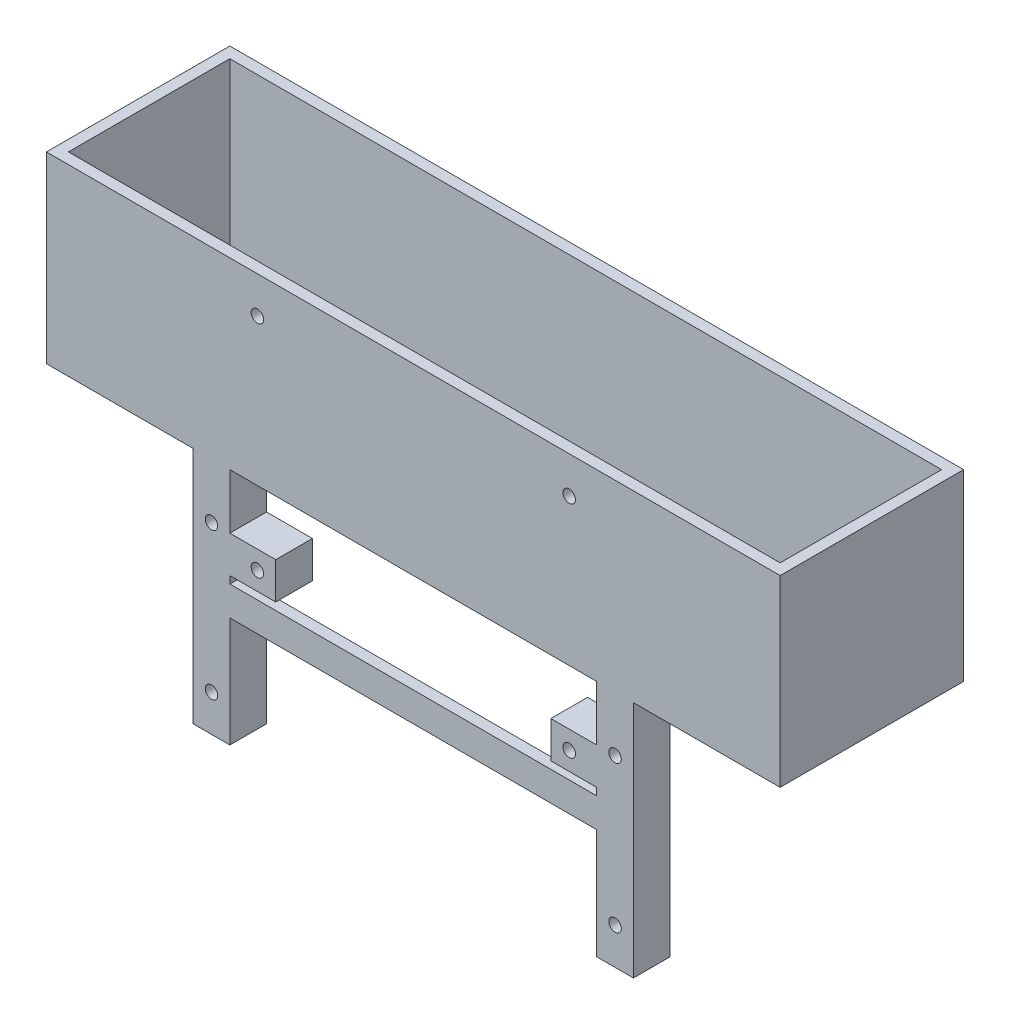
SolidWorks part; units mm, degrees
ref_plane "前视基准面" through (0, 0, 0) normal (0, 0, 1) x (1, 0, 0)
ref_plane "上视基准面" through (0, 0, 0) normal (0, 1, 0) x (1, 0, 0)
ref_plane "右视基准面" through (0, 0, 0) normal (1, 0, 0) x (0, 0, -1)
other "Configuration Table"
sketch "Box footprint 200 x 50 mm" plane through (0, 0, 0) normal (0, 0, 1) x (1, 0, 0)
  line L1 (-100, 0) -> (100, 0)
  line L2 (-100, 0) -> (-100, 50)
  line L3 (-100, 50) -> (100, 50)
  line L4 (100, 0) -> (100, 50)
extrude "Box height 50 mm" add sketch "Box footprint 200 x 50 mm" along normal blind 50
sketch "Rear opening 194 x 44 mm" plane through (0, 50, 0) normal (0, 1, 0) x (1, 0, 0)
  line L1 (-97, -3) -> (97, -3)
  line L2 (-97, -3) -> (-97, -47)
  line L3 (-97, -47) -> (97, -47)
  line L4 (97, -3) -> (97, -47)
extrude "Rear cavity wall 3 mm" cut sketch "Rear opening 194 x 44 mm" against normal blind 47
sketch "Chassis face openings and mounting crossbar" plane through (0, 0, 0) normal (0, -1, 0) x (1, 0, 0)
  line L1 (-97, 3) -> (-60, 3)
  line L2 (-97, 3) -> (-97, 47)
  line L3 (-97, 47) -> (-60, 47)
  line L4 (-60, 3) -> (-60, 47)
  line L6 (60, 3) -> (97, 3)
  line L7 (60, 3) -> (60, 47)
  line L8 (60, 47) -> (97, 47)
  line L9 (97, 3) -> (97, 47)
  line L11 (-50, 3) -> (50, 3)
  line L12 (-50, 3) -> (-50, 16)
  line L13 (-50, 16) -> (50, 16)
  line L14 (50, 3) -> (50, 16)
  line L16 (-50, 34) -> (50, 34)
  line L17 (-50, 34) -> (-50, 47)
  line L18 (-50, 47) -> (50, 47)
  line L19 (50, 34) -> (50, 47)
extrude "Open front mounting frame" cut sketch "Chassis face openings and mounting crossbar" against normal blind 3
sketch "Photo rails 10 x 10 pitch 110 provisional" plane through (0, 0, 0) normal (0, -1, 0) x (1, 0, 0)
  line L1 (-60, 40) -> (-50, 40)
  line L2 (-60, 40) -> (-60, 50)
  line L3 (-60, 50) -> (-50, 50)
  line L4 (-50, 40) -> (-50, 50)
  line L6 (50, 40) -> (60, 40)
  line L7 (50, 40) -> (50, 50)
  line L8 (50, 50) -> (60, 50)
  line L9 (60, 40) -> (60, 50)
extrude "Two forward rails 65 mm provisional" add sketch "Photo rails 10 x 10 pitch 110 provisional" along normal blind 65
sketch "Left inward PCB mounting ear" plane through (-50, 0, 0) normal (1, 0, 0) x (0, 0, -1)
  line L1 (-40, -25) -> (-50, -25)
  line L2 (-40, -25) -> (-40, -15)
  line L3 (-40, -15) -> (-50, -15)
  line L4 (-50, -25) -> (-50, -15)
extrude "Left PCB ear 12.5 mm" add sketch "Left inward PCB mounting ear" along normal blind 12.5
sketch "Right inward PCB mounting ear" plane through (50, 0, 0) normal (-1, 0, 0) x (0, 0, 1)
  line L1 (40, -25) -> (50, -25)
  line L2 (40, -25) -> (40, -15)
  line L3 (40, -15) -> (50, -15)
  line L4 (50, -25) -> (50, -15)
extrude "Right PCB ear 12.5 mm" add sketch "Right inward PCB mounting ear" along normal blind 12.5
sketch "Open frame transverse brace 8 x 3 mm" plane through (-50, 0, 0) normal (1, 0, 0) x (0, 0, -1)
  line L1 (-47, -35) -> (-50, -35)
  line L2 (-47, -35) -> (-47, -27)
  line L3 (-47, -27) -> (-50, -27)
  line L4 (-50, -35) -> (-50, -27)
extrude "Transverse frame brace" add sketch "Open frame transverse brace 8 x 3 mm" along normal blind 100
sketch "Chassis slot centers -50 -20 20 50 mm" plane through (0, 0, 0) normal (0, -1, 0) x (1, 0, 0)
  line L0 (-50, 21.7) -> (-50, 28.3) construction
  line L1 (-51.7, 21.7) -> (-51.7, 28.3)
  line L2 (-48.3, 21.7) -> (-48.3, 28.3)
  line L3 (-20, 21.7) -> (-20, 28.3) construction
  line L4 (-21.7, 21.7) -> (-21.7, 28.3)
  line L5 (-18.3, 21.7) -> (-18.3, 28.3)
  line L6 (20, 21.7) -> (20, 28.3) construction
  line L7 (18.3, 21.7) -> (18.3, 28.3)
  line L8 (21.7, 21.7) -> (21.7, 28.3)
  line L9 (50, 21.7) -> (50, 28.3) construction
  line L10 (48.3, 21.7) -> (48.3, 28.3)
  line L11 (51.7, 21.7) -> (51.7, 28.3)
  arc A0 (-51.7, 21.7) -> (-48.3, 21.7) centre (-50, 21.7) ccw
  arc A1 (-48.3, 28.3) -> (-51.7, 28.3) centre (-50, 28.3) ccw
  arc A2 (-21.7, 21.7) -> (-18.3, 21.7) centre (-20, 21.7) ccw
  arc A3 (-18.3, 28.3) -> (-21.7, 28.3) centre (-20, 28.3) ccw
  arc A4 (18.3, 21.7) -> (21.7, 21.7) centre (20, 21.7) ccw
  arc A5 (21.7, 28.3) -> (18.3, 28.3) centre (20, 28.3) ccw
  arc A6 (48.3, 21.7) -> (51.7, 21.7) centre (50, 21.7) ccw
  arc A7 (51.7, 28.3) -> (48.3, 28.3) centre (50, 28.3) ccw
  point P2 (-50, 25)
  point P7 (-20, 25)
  point P14 (20, 25)
  point P21 (50, 25)
  point P28 (0, 0)
  dimension "D1" = 3.4
  dimension "D2" = 6.6
  dimension "D3" = 3.4
  dimension "D4" = 6.6
  dimension "D5" = 3.4
  dimension "D6" = 6.6
  dimension "D7" = 3.4
  dimension "D8" = 6.6
extrude "4x vertical slots 3.4 x 10 mm" cut sketch "Chassis slot centers -50 -20 20 50 mm" against normal blind 3
sketch "PCB rear holes pitch 85 mm" plane through (0, 0, 50) normal (0, 0, 1) x (1, 0, 0)
  circle A0 centre (-42.5, 40) radius 1.7
  circle A1 centre (42.5, 40) radius 1.7
extrude "PCB roof holes diameter 3.4 mm" cut sketch "PCB rear holes pitch 85 mm" against normal blind 3
sketch "PCB front holes row spacing 60 mm" plane through (0, 0, 50) normal (0, 0, 1) x (1, 0, 0)
  circle A0 centre (-42.5, -20) radius 1.7
  circle A1 centre (42.5, -20) radius 1.7
extrude "PCB ear holes diameter 3.4 mm" cut sketch "PCB front holes row spacing 60 mm" against normal blind 10
sketch "Chassis top holes 110 x 40 provisional" plane through (0, 0, 50) normal (0, 0, 1) x (1, 0, 0)
  circle A0 centre (-55, -55) radius 1.7
  circle A1 centre (-55, -15) radius 1.7
  circle A2 centre (55, -55) radius 1.7
  circle A3 centre (55, -15) radius 1.7
extrude "4x rail holes through upper and lower faces" cut sketch "Chassis top holes 110 x 40 provisional" against normal blind 10
